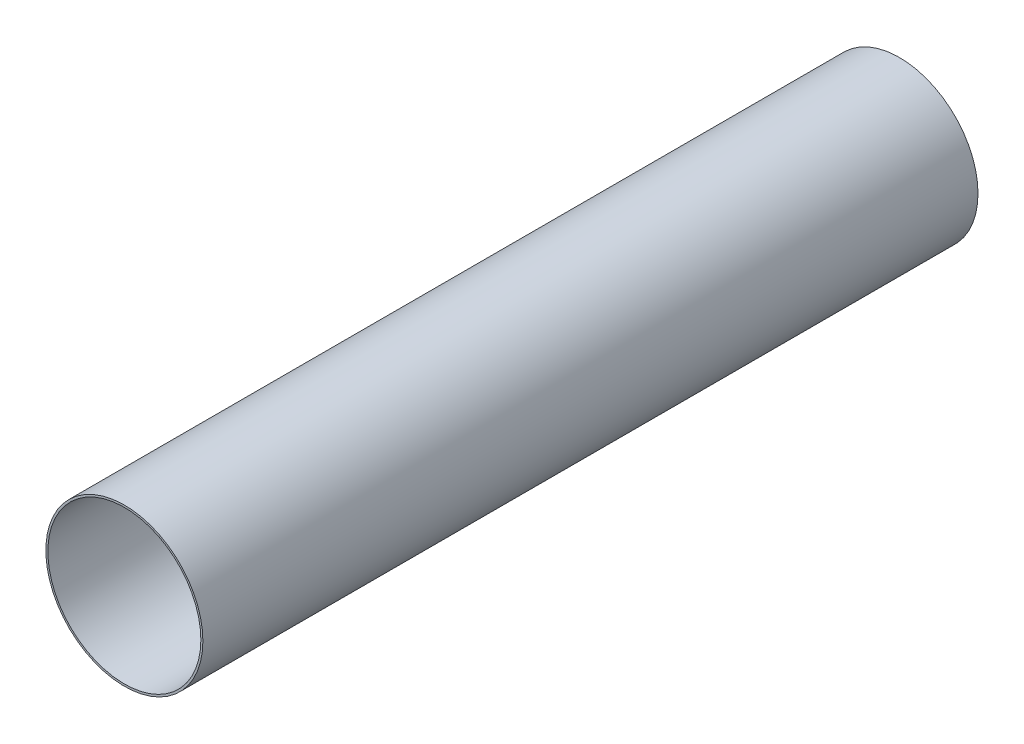
SolidWorks part; units mm, degrees
material "E-Glass Fiber"
ref_plane "Front" through (0, 0, 0) normal (0, 0, 1) x (1, 0, 0)
ref_plane "Top" through (0, 0, 0) normal (0, 1, 0) x (1, 0, 0)
ref_plane "Right" through (0, 0, 0) normal (1, 0, 0) x (0, 0, -1)
sketch "Sketch1" plane through (0, 0, 0) normal (0, 0, 1) x (1, 0, 0)
  circle A0 centre (0, 0) radius 78
  circle A1 centre (0, 0) radius 76
  dimension "D1" = 156
  dimension "D2" = 152
extrude "Boss-Extrude1" add sketch "Sketch1" along normal blind 770
